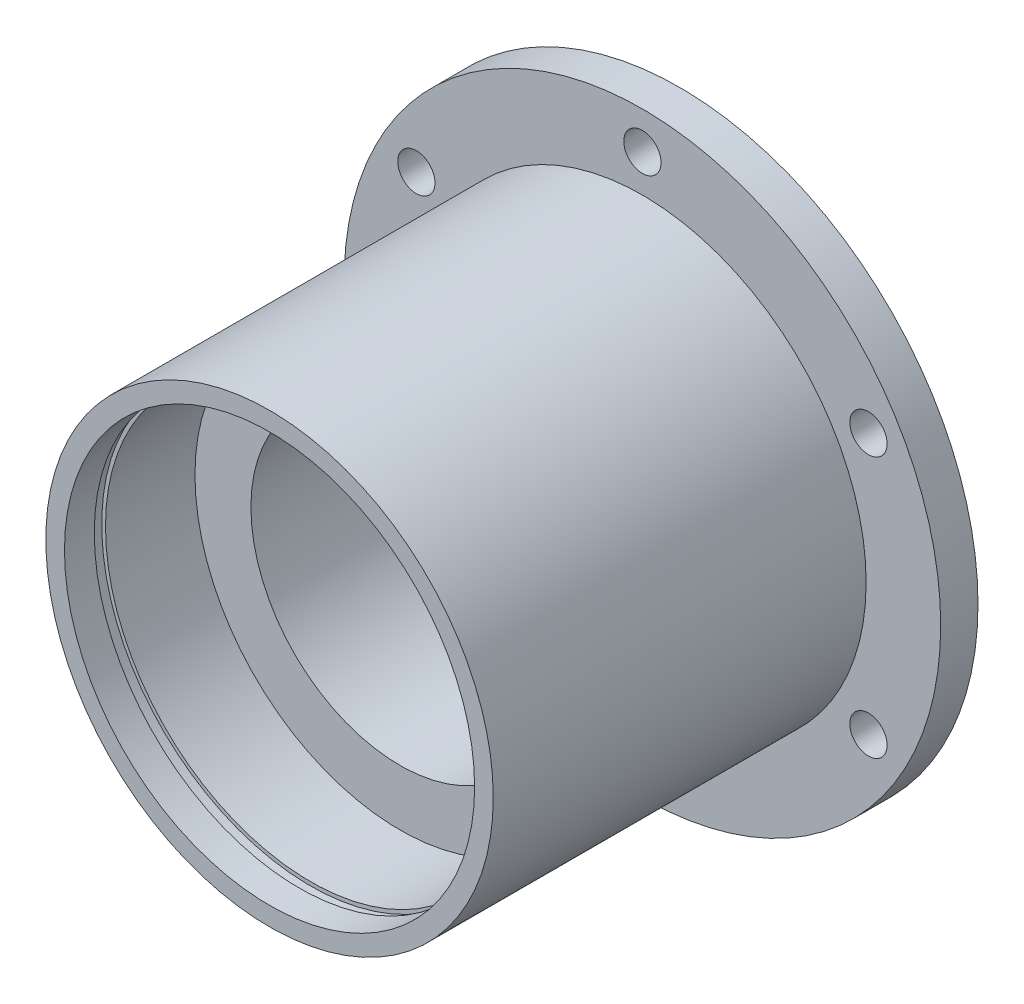
SolidWorks part; units mm, degrees
ref_plane "Front Plane" through (0, 0, 0) normal (0, 0, 1) x (1, 0, 0)
ref_plane "Top Plane" through (0, 0, 0) normal (0, 1, 0) x (1, 0, 0)
ref_plane "Right Plane" through (0, 0, 0) normal (1, 0, 0) x (0, 0, -1)
sketch "Sketch1" plane through (0, 0, 0) normal (0, 0, 1) x (1, 0, 0)
  line L0 (0, 35) -> (0, 0) construction
  circle A0 centre (0, 0) radius 40
  circle A1 centre (0, 35) radius 2.5
  circle A2 centre (30.3109, 17.5) radius 2.5
  circle A3 centre (30.3109, -17.5) radius 2.5
  circle A4 centre (0, -35) radius 2.5
  circle A5 centre (-30.3109, -17.5) radius 2.5
  circle A6 centre (-30.3109, 17.5) radius 2.5
  point P18 (0, 0)
  dimension "D1" = 80
  dimension "D2" = 35
  dimension "D3" = 6
extrude "Boss-Extrude1" add sketch "Sketch1" along normal blind 5
sketch "Sketch2" plane through (0, 0, 5) normal (0, 0, 1) x (1, 0, 0)
  circle A0 centre (0, 0) radius 30
  circle A1 centre (0, 0) radius 27.5
  dimension "D1" = 60
  dimension "D2" = 55
extrude "Boss-Extrude2" add sketch "Sketch2" along normal blind 50
sketch "Sketch3" plane through (0, 0, 0) normal (0, 0, -1) x (-1, 0, 0)
  circle A0 centre (0, 0) radius 27.5
  dimension "D1" = 55
extrude "Cut-Extrude1" cut sketch "Sketch3" against normal blind 50
ref_plane "Plane1" through (0, 0, 27.5) normal (0, 0, -1) x (-1, 0, 0)
sketch "Sketch5" plane through (0, 0, 27.5) normal (0, 0, -1) x (-1, 0, 0)
  circle A0 centre (0, 0) radius 27.5
  circle A1 centre (0, 0) radius 20
  dimension "D1" = 40
extrude "Boss-Extrude4" add sketch "Sketch5" along normal blind 10 and the other way blind 10
sketch "Sketch6" plane through (0, 0, 17.5) normal (0, 0, -1) x (-1, 0, 0)
  circle A0 centre (0, 0) radius 28
  dimension "D1" = 56
extrude "Cut-Extrude2" cut sketch "Sketch6" along normal offset from surface (1.5 mm away) 4 from offset 12 up to face at (-27.5, 0, 0)
sketch "Sketch7" plane through (0, 0, 37.5) normal (0, 0, 1) x (1, 0, 0)
  circle A0 centre (0, 0) radius 28
extrude "Cut-Extrude3" cut sketch "Sketch7" along normal offset from surface (1.5 mm away) 4 from offset 12 up to face at (30, 0, 55)
